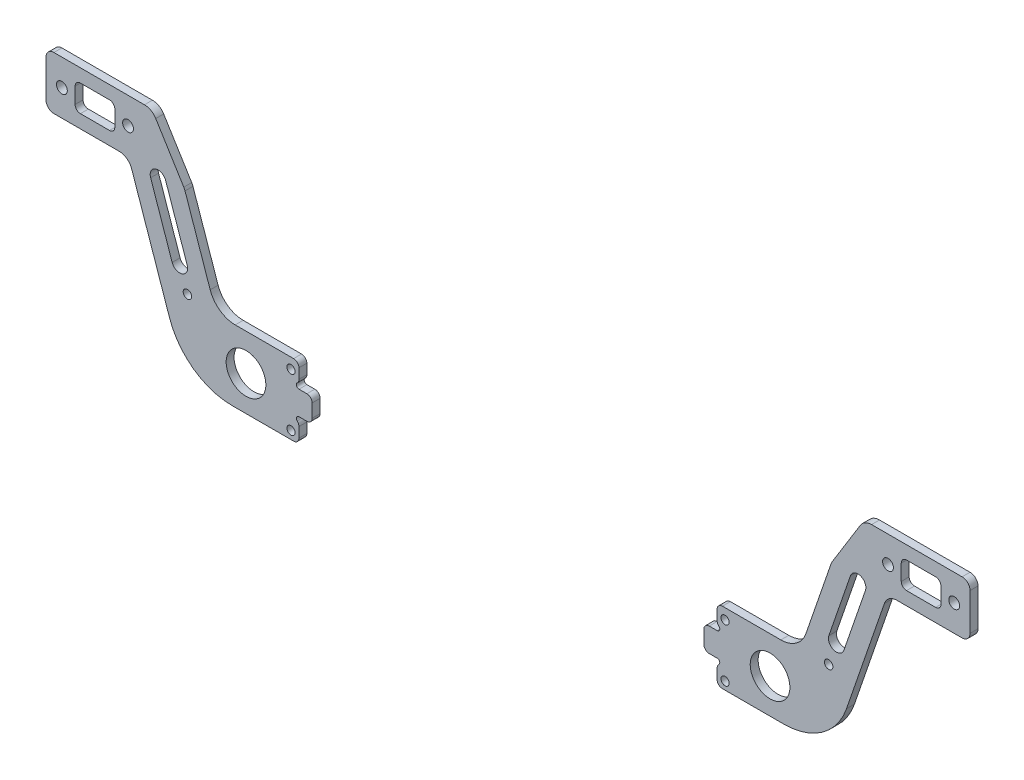
SolidWorks part; units mm, degrees
material "Thornel Mat VMA"
ref_plane "前视基准面" through (0, 0, 0) normal (0, 0, 1) x (1, 0, 0)
ref_plane "上视基准面" through (0, 0, 0) normal (0, 1, 0) x (1, 0, 0)
ref_plane "右视基准面" through (0, 0, 0) normal (1, 0, 0) x (0, 0, -1)
sketch "草图1" plane through (0, 0, 0) normal (0, 0, 1) x (1, 0, 0)
  line L1 (-98, -24.835) -> (98, -24.835)
  line L2 (-98, -24.835) -> (-98, 24.835)
  line L3 (-98, 24.835) -> (98, 24.835)
  line L4 (98, -24.835) -> (98, 24.835)
  line L5 (-98, -24.835) -> (98, 24.835) construction
  line L6 (-98, 24.835) -> (98, -24.835) construction
  point P0 (0, 0)
  dimension "D1" = 196
  dimension "D2" = 49.67
extrude "凸台-拉伸1" add sketch "草图1" along normal blind 3
sketch "草图2" plane through (0, 0, 3) normal (0, 0, 1) x (1, 0, 0)
  line L0 (98, 24.835) -> (114, 24.835)
  line L1 (114, 24.835) -> (122.2225, 48.715)
  line L2 (134.5666, 68.715) -> (174.5666, 68.715)
  line L3 (174.5666, 68.715) -> (174.5666, 48.715)
  line L4 (174.5666, 48.715) -> (143.375, 48.715)
  line L5 (143.375, 48.715) -> (128.2659, 4.835)
  line L6 (128.2659, 4.835) -> (98, 4.835)
  line L7 (98, -24.835) -> (98, 24.835) construction
  line L8 (98, 24.835) -> (98, 4.835)
  line L9 (0, 0) -> (0, 24.835) construction
  line L10 (98, 24.835) -> (-98, 24.835) construction
  line L11 (-98, 24.835) -> (-98, 4.835)
  line L12 (-128.2659, 4.835) -> (-98, 4.835)
  line L13 (-143.375, 48.715) -> (-128.2659, 4.835)
  line L14 (-174.5666, 48.715) -> (-143.375, 48.715)
  line L15 (-174.5666, 68.715) -> (-174.5666, 48.715)
  line L16 (-134.5666, 68.715) -> (-174.5666, 68.715)
  line L17 (-114, 24.835) -> (-122.2225, 48.715)
  line L18 (-98, 24.835) -> (-114, 24.835)
  line L19 (122.2225, 48.715) -> (143.375, 48.715) construction
  line L20 (-122.2225, 48.715) -> (-143.375, 48.715) construction
  line L21 (122.2225, 48.715) -> (134.5666, 68.715)
  line L23 (-122.2225, 48.715) -> (-134.5666, 68.715)
  dimension "D1" = 114
  dimension "D2" = 109
  dimension "D3" = 20
  dimension "D4" = 20
  dimension "D5" = 20
  dimension "D6" = 43.88
  dimension "D7" = 40
  dimension "D8" = 18
extrude "凸台-拉伸2" add sketch "草图2" against normal up to surface (3 mm away) up to face at (0, 0, 0)
fillet "圆角1" radius 10 4 edges at (128.2659, 4.835, 1.5) (114, 24.835, 1.5) (-128.2659, 4.835, 1.5) (-114, 24.835, 1.5)
fillet "圆角2" radius 3 6 edges at (-174.5666, 48.715, 1.5) (-174.5666, 68.715, 1.5) (174.5666, 68.715, 1.5) (174.5666, 48.715, 1.5) (98, -24.835, 1.5) (-98, -24.835, 1.5)
sketch "草图3" plane through (0, 0, 3) normal (0, 0, 1) x (1, 0, 0)
  line L0 (98, -21.835) -> (98, 4.835) construction
  line L1 (-88, -15) -> (88, -15) construction
  line L2 (-88, -15) -> (-88, 15) construction
  line L3 (-88, 15) -> (88, 15) construction
  line L4 (88, -15) -> (88, 15) construction
  line L5 (-88, -15) -> (88, 15) construction
  line L6 (-88, 15) -> (88, -15) construction
  circle A0 centre (88, -15) radius 1.6
  circle A1 centre (88, 15) radius 1.6
  circle A2 centre (-88, 15) radius 1.6
  circle A3 centre (-88, -15) radius 1.6
  point P0 (0, 0)
  dimension "D3" = 3.2
  dimension "D1" = 10
  dimension "D2" = 30
sketch "草图4" plane through (0, 0, 3) normal (0, 0, 1) x (1, 0, 0)
  line L0 (0, 5.1613) -> (0, 0) construction
  line L1 (47.5, -7.3387) -> (-47.5, -7.3387) construction
  line L2 (47.5, -7.3387) -> (47.5, 17.6613) construction
  line L3 (47.5, 17.6613) -> (-47.5, 17.6613) construction
  line L4 (-47.5, -7.3387) -> (-47.5, 17.6613) construction
  line L5 (47.5, -7.3387) -> (-47.5, 17.6613) construction
  line L6 (47.5, 17.6613) -> (-47.5, -7.3387) construction
  circle A2 centre (47.5, -7.3387) radius 2.1
  circle A3 centre (47.5, 17.6613) radius 2.1
  circle A4 centre (-47.5, 17.6613) radius 2.1
  circle A5 centre (-47.5, -7.3387) radius 2.1
  point P6 (0, 5.1613)
  dimension "D4" = 4.2
  dimension "D1" = 95
  dimension "D2" = 25
  dimension "D3" = 5.1613
extrude "切除-拉伸2" cut sketch "草图4" against normal blind 4
fillet "圆角3" radius 5 6 edges at (122.2225, 48.715, 1.5) (-122.2225, 48.715, 1.5) (-134.5666, 68.715, 1.5) (-143.375, 48.715, 1.5) (134.5666, 68.715, 1.5) (143.375, 48.715, 1.5)
sketch "草图5" [suppressed] plane through (0, 0, 4) normal (0, 0, 1) x (1, 0, 0)
  line L0 (0, 0) -> (0, -20.895) construction
  line L1 (0, -20.895) -> (27.5, -20.895) construction
  line L2 (-98, -24.835) -> (98, -24.835) construction
  circle A0 centre (27.5, -20.895) radius 1.55
  circle A1 centre (-27.5, -20.895) radius 1.55
  dimension "D3" = 3.1
  dimension "D1" = 27.5
  dimension "D2" = 3.94
extrude "切除-拉伸3" [suppressed] cut sketch "草图5" against normal blind 10
sketch "草图6" plane through (0, 0, 3) normal (0, 0, 1) x (1, 0, 0)
  line L0 (-174.5666, 58.715) -> (-128.3946, 58.715) construction
  line L1 (-174.5666, 65.715) -> (-174.5666, 51.715) construction
  line L2 (-122.5144, 49.1879) -> (-133.1014, 66.3411) construction
  line L3 (0, 0) -> (0, 128.8135) construction
  line L4 (174.5666, 58.715) -> (128.3946, 58.715) construction
  circle A0 centre (-168.5666, 58.715) radius 2.05
  circle A1 centre (-143.5666, 58.715) radius 2.05
  circle A2 centre (143.5666, 58.715) radius 2.05
  circle A3 centre (168.5666, 58.715) radius 2.05
  dimension "D1" = 4.1
  dimension "D2" = 6
  dimension "D3" = 25
extrude "切除-拉伸4" cut sketch "草图6" against normal blind 10
sketch "草图7" plane through (0, 0, 3) normal (0, 0, 1) x (1, 0, 0)
  line L0 (-174.5666, 58.715) -> (-136.4981, 58.715) construction
  line L1 (-174.5666, 65.715) -> (-174.5666, 51.715) construction
  line L2 (0, 0) -> (0, 175.8145) construction
  line L3 (174.5666, 58.715) -> (136.4981, 58.715) construction
  circle A0 centre (-168.5666, 58.715) radius 2.05
  circle A1 centre (-143.5666, 58.715) radius 2.05
  circle A2 centre (143.5666, 58.715) radius 2.05
  circle A3 centre (168.5666, 58.715) radius 2.05
  dimension "D1" = 4.1
  dimension "D2" = 6
  dimension "D3" = 25
extrude "切除-拉伸5" [suppressed] cut sketch "草图7" against normal blind 102
sketch "草图8" [suppressed] plane through (0, 0, 4) normal (0, 0, 1) x (1, 0, 0)
  line L0 (106.8671, 24.835) -> (-106.8671, 24.835) construction
  line L1 (-40, -15.895) -> (40, -15.895)
  line L2 (-40, -15.895) -> (-40, 18.835)
  line L3 (-40, 18.835) -> (40, 18.835)
  line L4 (40, -15.895) -> (40, 18.835)
  line L5 (-40, -15.895) -> (40, 18.835) construction
  line L6 (-40, 18.835) -> (40, -15.895) construction
  line L7 (0, 1.47) -> (0, 18.835) construction
  line L8 (0, 5.835) -> (-40, -15.895) construction
  line L9 (0, 5.835) -> (40, -15.895) construction
  line L10 (3, 1.47) -> (3, 18.835)
  line L11 (0, 9.2491) -> (41.4321, -13.2589)
  line L12 (0, 9.2491) -> (-41.4321, -13.2589)
  line L13 (-3, 1.47) -> (-3, 18.835)
  line L14 (0, 2.4209) -> (38.5679, -18.5311)
  line L15 (0, 2.4209) -> (-38.5679, -18.5311)
  circle A0 centre (-27.5, -20.895) radius 1.55 construction
  circle A1 centre (-47.5, -7.3387) radius 2.1 construction
  point P0 (0, 1.47)
  dimension "D2" = 7.5
  dimension "D1" = 5
  dimension "D3" = 6
  dimension "D4" = 13
  dimension "D5" = 3
  dimension "D6" = 3
extrude "切除-拉伸8" [suppressed] cut sketch "草图8" against normal blind 10 contours L12 L13 L3 L2 | L14 L15 L1 | L10 L11 L4 L3
fillet "圆角4" [suppressed] radius 3
sketch "草图10" plane through (0, 0, 3) normal (0, 0, 1) x (1, 0, 0)
  line L0 (106.8671, 24.835) -> (-106.8671, 24.835) construction
  line L1 (-40, -17.835) -> (40, -17.835)
  line L2 (-40, -17.835) -> (-40, 18.835)
  line L3 (-40, 18.835) -> (40, 18.835)
  line L4 (40, -17.835) -> (40, 18.835)
  line L5 (-40, -17.835) -> (40, 18.835) construction
  line L6 (-40, 18.835) -> (40, -17.835) construction
  line L7 (-95, -24.835) -> (95, -24.835) construction
  line L8 (0, 18.835) -> (0, 6.835) construction
  line L9 (0, 6.835) -> (-40, -17.835) construction
  line L10 (0, 6.835) -> (40, -17.835) construction
  line L11 (-3, 18.835) -> (-3, 6.835)
  line L12 (-1.5748, 9.3884) -> (-41.5748, -15.2816)
  line L13 (-1.5748, 4.2816) -> (38.4252, -20.3884)
  line L14 (3, 18.835) -> (3, 6.835)
  line L15 (1.5748, 4.2816) -> (-38.4252, -20.3884)
  line L16 (1.5748, 9.3884) -> (41.5748, -15.2816)
  circle A0 centre (-47.5, -7.3387) radius 2.1 construction
  circle A1 centre (47.5, 17.6613) radius 2.1 construction
  point P0 (0, 0.5)
  dimension "D1" = 6
  dimension "D2" = 7
  dimension "D3" = 7.5
  dimension "D4" = 7.5
  dimension "D5" = 12
  dimension "D6" = 3
  dimension "D7" = 3
extrude "切除-拉伸10" cut sketch "草图10" against normal blind 10 contours L13 L15 L1 | L12 L11 L3 L2 | L14 L16 L4 L3
fillet "圆角7" radius 2 11 edges at (-40, 18.835, 1.5) (-3, 18.835, 1.5) (-3, 8.5094, 1.5) (34.2851, -17.835, 1.5) (3, 18.835, 1.5) (40, 18.835, 1.5) (40, -14.3103, 1.5) (3, 8.5094, 1.5) (-34.2851, -17.835, 1.5) (-40, -14.3103, 1.5) (0, 3.3103, 1.5)
sketch "草图13" plane through (0, 0, 3) normal (0, 0, 1) x (1, 0, 0)
  line L0 (106.8671, 24.835) -> (-106.8671, 24.835) construction
  line L1 (-98, 4.835) -> (-104, 4.835)
  line L2 (-98, 4.835) -> (-98, -15.165)
  line L3 (-98, -15.165) -> (-104, -15.165)
  line L4 (-104, 4.835) -> (-104, -15.165)
  dimension "D1" = 40
  dimension "D2" = 6
extrude "凸台-拉伸3" add sketch "草图13" against normal up to surface (3 mm away) up to face at (21.2723, 8.1928, 0)
mirror "镜向3" about plane through (0, 0, 0) normal (1, 0, 0) of "凸台-拉伸3"
fillet "圆角9" radius 10 2 edges at (104, 4.835, 1.5) (-104, 4.835, 1.5)
fillet "圆角10" radius 2 4 edges at (104, -15.165, 1.5) (98, -15.165, 1.5) (-98, -15.165, 1.5) (-104, -15.165, 1.5)
sketch "草图14" plane through (0, 0, 0) normal (0, 0, -1) x (-1, 0, 0)
  line L0 (104, 24.835) -> (104, 9.835) construction
  line L1 (-106.8671, 24.835) -> (106.8671, 24.835) construction
  line L2 (104, 9.835) -> (104, -10.165) construction
  circle A2 centre (104, 9.835) radius 1.55
  circle A3 centre (104, -10.165) radius 1.55
  dimension "D4" = 3.1
  dimension "D1" = 104
  dimension "D2" = 15
  dimension "D3" = 20
extrude "切除-拉伸12" cut sketch "草图14" against normal blind 10
mirror "镜向4" about plane through (0, 0, 0) normal (1, 0, 0) of "切除-拉伸12"
sketch "草图15" [suppressed] plane through (0, 0, 0) normal (0, 0, -1) x (-1, 0, 0)
  line L0 (-106.8671, 24.835) -> (106.8671, 24.835) construction
  line L1 (-101, 4.835) -> (-107, 4.835)
  line L2 (-101, 4.835) -> (-101, -15.165)
  line L3 (-101, -15.165) -> (-107, -15.165)
  line L4 (-107, 4.835) -> (-107, -15.165)
  dimension "D1" = 40
  dimension "D2" = 6
extrude "凸台-拉伸4" [suppressed] add sketch "草图15" against normal up to surface (4 mm away)
mirror "镜向5" [suppressed] about plane through (0, 0, 0) normal (1, 0, 0)
fillet "圆角11" [suppressed] radius 10
fillet "圆角12" [suppressed] radius 2
sketch "草图16" [suppressed] plane through (0, 0, 4) normal (0, 0, 1) x (1, 0, 0)
  line L0 (0, 0) -> (104, 0) construction
  line L1 (104, 0) -> (104, 9.835) construction
  line L2 (104, 0) -> (104, -10.165) construction
  circle A2 centre (104, -10.165) radius 1.6
  circle A3 centre (104, 9.835) radius 1.6
  dimension "D4" = 3.2
  dimension "D1" = 104
  dimension "D2" = 9.835
  dimension "D3" = 10.165
extrude "切除-拉伸13" [suppressed] cut sketch "草图16" against normal blind 10
mirror "镜向6" [suppressed] about plane through (0, 0, 0) normal (1, 0, 0)
sketch "草图21" plane through (0, 0, 3) normal (0, 0, 1) x (1, 0, 0)
  line L0 (-114, 4.835) -> (-98, 4.835)
  line L1 (-98, 4.835) -> (-98, -17.165)
  line L2 (-114, 4.835) -> (-114, -17.165)
  line L3 (-114, -17.165) -> (-98, -17.165)
extrude "切除-拉伸16" cut sketch "草图21" against normal blind 10
sketch "草图22" plane through (0, 0, 3) normal (0, 0, 1) x (1, 0, 0)
  circle A0 centre (-104, 9.835) radius 1.55 construction
  circle A1 centre (-104, 9.835) radius 1.55
extrude "凸台-拉伸5" add sketch "草图22" against normal up to surface (3 mm away) up to face at (17.7653, 26.7306, 0)
fillet "圆角13" radius 10 1 edges at (-98, 4.835, 1.5)
mirror "镜向9" about plane through (0, 0, 0) normal (1, 0, 0) of "切除-拉伸16", "凸台-拉伸5", "圆角13"
sketch "草图23" [suppressed] plane through (0, 0, 4) normal (0, 0, 1) x (1, 0, 0)
  line L0 (-117, 4.835) -> (-101, 4.835)
  line L1 (-101, 4.835) -> (-101, -17.165)
  line L2 (-117, 4.835) -> (-117, -17.165)
  line L3 (-117, -17.165) -> (-101, -17.165)
  line L4 (0, -0.9932) -> (0, 64.1074) construction
  line L5 (117, -17.165) -> (101, -17.165)
  line L6 (117, 4.835) -> (117, -17.165)
  line L7 (101, 4.835) -> (101, -17.165)
  line L8 (117, 4.835) -> (101, 4.835)
extrude "切除-拉伸17" [suppressed] cut sketch "草图23" against normal blind 10
sketch "草图24" [suppressed] plane through (0, 0, 4) normal (0, 0, 1) x (1, 0, 0)
  circle A0 centre (104, 9.835) radius 1.6 construction
  circle A1 centre (-104, 9.835) radius 1.6 construction
  circle A2 centre (104, 9.835) radius 1.6
  circle A3 centre (-104, 9.835) radius 1.6
extrude "凸台-拉伸6" [suppressed] add sketch "草图24" against normal up to surface (4 mm away)
fillet "圆角14" [suppressed] radius 10
sketch "草图25" plane through (0, 0, 3) normal (0, 0, 1) x (1, 0, 0)
  line L0 (-168.7548, 58.715) -> (-143.3784, 58.715) construction
  line L1 (0, 0) -> (0, 119.1313) construction
  line L8 (-163.5666, 53.715) -> (-148.5666, 53.715)
  line L9 (-163.5666, 53.715) -> (-163.5666, 63.715)
  line L10 (-163.5666, 63.715) -> (-148.5666, 63.715)
  line L11 (-148.5666, 53.715) -> (-148.5666, 63.715)
  line L12 (-156.0666, 63.715) -> (-156.0666, 53.715) construction
  line L13 (-163.5666, 58.715) -> (-148.5666, 58.715) construction
  line L14 (163.5666, 63.715) -> (148.5666, 63.715)
  line L15 (148.5666, 53.715) -> (148.5666, 63.715)
  line L16 (163.5666, 53.715) -> (148.5666, 53.715)
  line L17 (163.5666, 53.715) -> (163.5666, 63.715)
  point P2 (-156.0666, 58.715)
extrude "切除-拉伸18" cut sketch "草图25" against normal blind 10
sketch "草图26" plane through (0, 0, 3) normal (0, 0, 1) x (1, 0, 0)
  line L0 (116.3223, 31.5793) -> (110.2124, 13.835)
  line L1 (-98, 35) -> (98, 35)
  line L2 (-98, 35) -> (-98, -35)
  line L3 (-98, -35) -> (98, -35)
  line L4 (98, 35) -> (98, -35)
  line L5 (-98, 35) -> (98, -35) construction
  line L6 (-98, -35) -> (98, 35) construction
  line L7 (130.5881, 11.5793) -> (122.068, -13.165)
  line L8 (130.5881, 11.5793) -> (142.2138, 45.3428) construction
  line L9 (122.068, -13.165) -> (74, -13.165)
  line L10 (74, -13.165) -> (74, 13.835)
  line L11 (74, 13.835) -> (110.2124, 13.835)
  line L12 (130.5881, 11.5793) -> (116.3223, 31.5793)
  line L13 (106.8671, 24.835) -> (-106.8671, 24.835) construction
  line L14 (106.8671, 24.835) -> (-106.8671, 24.835)
  line L15 (0, -63.4522) -> (0, 61.7142) construction
  line L16 (122.0416, 48.1896) -> (116.3223, 31.5793) construction
  line L17 (-130.5881, 11.5793) -> (-122.068, -13.165)
  line L18 (-122.068, -13.165) -> (-74, -13.165)
  line L19 (-74, -13.165) -> (-74, 13.835)
  line L20 (-74, 13.835) -> (-110.2124, 13.835)
  line L21 (-116.3223, 31.5793) -> (-110.2124, 13.835)
  line L22 (-130.5881, 11.5793) -> (-116.3223, 31.5793)
  line L23 (98, -21.835) -> (98, -5.165) construction
  arc A0 (-116.3223, 31.5793) -> (-106.8671, 24.835) centre (-106.8671, 34.835) ccw construction
  arc A1 (106.8671, 24.835) -> (116.3223, 31.5793) centre (106.8671, 34.835) ccw construction
  arc A2 (-116.3223, 31.5793) -> (-106.8671, 24.835) centre (-106.8671, 34.835) ccw
  arc A3 (106.8671, 24.835) -> (116.3223, 31.5793) centre (106.8671, 34.835) ccw
  point P0 (0, 0)
  dimension "D1" = 27
  dimension "D2" = 24
  dimension "D3" = 11
  dimension "D4" = 70
extrude "切除-拉伸19" cut sketch "草图26" against normal mid plane 10 contours L20 L19 L18 L2 L3 L4 L9 L10 L11 L14 | A3 L14 L4 L11 L0 | A2 L21 L20 L2 L14
sketch "草图27" plane through (0, 0, 3) normal (0, 0, 1) x (1, 0, 0)
  line L14 (116.3223, 31.5793) -> (110.2124, 13.835)
  line L15 (110.2124, 13.835) -> (74, 13.835)
  line L16 (74, 13.835) -> (74, -13.165)
  line L17 (74, -13.165) -> (122.068, -13.165)
  line L18 (122.068, -13.165) -> (130.5881, 11.5793)
  line L19 (130.5881, 11.5793) -> (116.3223, 31.5793)
  line L20 (116.3223, 31.5793) -> (112.5347, 20.5793)
  line L21 (103.0795, 13.835) -> (74, 13.835)
  line L22 (74, 13.835) -> (74, -13.165)
  line L23 (74, -13.165) -> (104.2356, -13.165)
  line L24 (127.8736, 3.6958) -> (130.5881, 11.5793)
  line L25 (130.5881, 11.5793) -> (116.3223, 31.5793)
  line L26 (-130.5881, 11.5793) -> (-122.068, -13.165)
  line L27 (-122.068, -13.165) -> (-74, -13.165)
  line L28 (-74, -13.165) -> (-74, 13.835)
  line L29 (-74, 13.835) -> (-110.2124, 13.835)
  line L30 (-110.2124, 13.835) -> (-116.3223, 31.5793)
  line L31 (-116.3223, 31.5793) -> (-130.5881, 11.5793)
  line L32 (-130.5881, 11.5793) -> (-127.8736, 3.6958)
  line L33 (-104.2356, -13.165) -> (-74, -13.165)
  line L34 (-74, -13.165) -> (-74, 13.835)
  line L35 (-74, 13.835) -> (-103.0795, 13.835)
  line L36 (-112.5347, 20.5793) -> (-116.3223, 31.5793)
  line L37 (-116.3223, 31.5793) -> (-130.5881, 11.5793)
  arc A1 (112.5347, 20.5793) -> (103.0795, 13.835) centre (103.0795, 23.835) cw
  arc A3 (-103.0795, 13.835) -> (-112.5347, 20.5793) centre (-103.0795, 23.835) cw
  arc A4 (-127.8736, 3.6958) -> (-104.2356, -13.165) centre (-104.2356, 11.835) ccw
  arc A5 (104.2356, -13.165) -> (127.8736, 3.6958) centre (104.2356, 11.835) ccw
  dimension "D4" = 10
  dimension "D5" = 25
  dimension "D2" = 0
  dimension "D3" = 0
extrude "凸台-拉伸7" add sketch "草图27" against normal blind 3
sketch "草图28" plane through (0, 0, 3) normal (0, 0, 1) x (1, 0, 0)
  line L0 (106.8671, 24.835) -> (-106.8671, 24.835) construction
  line L1 (106.8671, 24.835) -> (-106.8671, 24.835)
  line L2 (82, -10.165) -> (82, 9.835) construction
  line L3 (0, -63.4522) -> (0, 61.7142) construction
  line L4 (98, 35) -> (-98, 35)
  line L5 (98, -35) -> (98, 35)
  line L6 (-98, -35) -> (98, -35)
  line L7 (-98, 35) -> (-98, -35)
  line L8 (98, 35) -> (-98, 35)
  line L9 (98, -35) -> (98, 35)
  line L10 (-98, -35) -> (98, -35)
  line L11 (-98, 35) -> (-98, -35)
  line L12 (0, -63.4522) -> (0, 61.7142)
  line L14 (116.3223, 31.5793) -> (110.2124, 13.835)
  line L15 (110.2124, 13.835) -> (74, 13.835)
  line L16 (74, 13.835) -> (74, -13.165)
  line L17 (74, -13.165) -> (122.068, -13.165)
  line L18 (122.068, -13.165) -> (130.5881, 11.5793)
  line L19 (130.5881, 11.5793) -> (116.3223, 31.5793)
  line L20 (116.3223, 31.5793) -> (110.2124, 13.835)
  line L21 (110.2124, 13.835) -> (74, 13.835)
  line L22 (74, 13.835) -> (74, -13.165)
  line L23 (74, -13.165) -> (122.068, -13.165)
  line L24 (122.068, -13.165) -> (130.5881, 11.5793)
  line L25 (130.5881, 11.5793) -> (116.3223, 31.5793)
  line L26 (-130.5881, 11.5793) -> (-122.068, -13.165)
  line L27 (-122.068, -13.165) -> (-74, -13.165)
  line L28 (-74, -13.165) -> (-74, 13.835)
  line L29 (-74, 13.835) -> (-110.2124, 13.835)
  line L30 (-110.2124, 13.835) -> (-116.3223, 31.5793)
  line L31 (-116.3223, 31.5793) -> (-130.5881, 11.5793)
  line L32 (-130.5881, 11.5793) -> (-122.068, -13.165)
  line L33 (-122.068, -13.165) -> (-74, -13.165)
  line L34 (-74, -13.165) -> (-74, 13.835)
  line L35 (-74, 13.835) -> (-110.2124, 13.835)
  line L36 (-110.2124, 13.835) -> (-116.3223, 31.5793)
  line L37 (-116.3223, 31.5793) -> (-130.5881, 11.5793)
  arc A0 (-116.3223, 31.5793) -> (-106.8671, 24.835) centre (-106.8671, 34.835) ccw construction
  arc A1 (106.8671, 24.835) -> (116.3223, 31.5793) centre (106.8671, 34.835) ccw construction
  arc A2 (-116.3223, 31.5793) -> (-106.8671, 24.835) centre (-106.8671, 34.835) ccw
  arc A3 (106.8671, 24.835) -> (116.3223, 31.5793) centre (106.8671, 34.835) ccw
  circle A4 centre (82, 9.835) radius 1.55
  circle A5 centre (82, -10.165) radius 1.55
  circle A6 centre (-82, 9.835) radius 1.55
  circle A7 centre (-82, -10.165) radius 1.55
  dimension "D6" = 3.1
  dimension "D4" = 8
  dimension "D5" = 20
  dimension "D7" = 15
  dimension "D1" = 0
  dimension "D2" = 0
  dimension "D3" = 0
extrude "切除-拉伸20" cut sketch "草图28" against normal blind 3 contours A4 | A5 | A7 | A6
sketch "草图29" plane through (0, 0, 3) normal (0, 0, 1) x (1, 0, 0)
  line L0 (0, -27.1496) -> (0, 41.7148) construction
  line L1 (74, 13.835) -> (79, 13.835)
  line L2 (74, 13.835) -> (74, 4.835)
  line L3 (74, 4.835) -> (79, 4.835)
  line L4 (79, 13.835) -> (79, 4.835)
  line L5 (74, -13.165) -> (79, -13.165)
  line L6 (74, -13.165) -> (74, -4.165)
  line L7 (74, -4.165) -> (79, -4.165)
  line L8 (79, -13.165) -> (79, -4.165)
  line L9 (-79, -13.165) -> (-79, -4.165)
  line L10 (-74, -4.165) -> (-79, -4.165)
  line L11 (-74, -13.165) -> (-74, -4.165)
  line L12 (-74, -13.165) -> (-79, -13.165)
  line L13 (-79, 13.835) -> (-79, 4.835)
  line L14 (-74, 4.835) -> (-79, 4.835)
  line L15 (-74, 13.835) -> (-74, 4.835)
  line L16 (-74, 13.835) -> (-79, 13.835)
  circle A0 centre (79, 5.835) radius 1
  circle A1 centre (79, -5.165) radius 1
  circle A2 centre (-79, -5.165) radius 1
  circle A3 centre (-79, 5.835) radius 1
  line M20 (103.0795, 13.835) -> (74, 13.835)
  line M21 (74, 13.835) -> (74, -13.165)
  line M22 (74, -13.165) -> (104.2356, -13.165)
  dimension "D3" = 2
  dimension "D1" = 5
  dimension "D2" = 9
extrude "切除-拉伸21" cut sketch "草图29" against normal blind 5 contours A1 L7 L8 M21 M22 | L8 A1 | L8 A1 | A0 L4 L3 M20 M21 | L4 A0 | L4 A0 | L13 A3 L14 L15 L16 | A3 L13 | A3 L13 | A2 L9 | A2 L9 | L10 A2 L9 L12 L11
sketch "草图30" plane through (0, 0, 0) normal (0, 0, -1) x (-1, 0, 0)
  circle A0 centre (121.1329, 14.835) radius 1.6
  circle A1 centre (-121.1329, 14.835) radius 1.6
  dimension "D1" = 3.2
extrude "切除-拉伸22" cut sketch "草图30" against normal blind 10
fillet "圆角15" radius 2 10 edges at (-148.5666, 53.715, 1.5) (-163.5666, 53.715, 1.5) (-148.5666, 63.715, 1.5) (-79, 13.835, 1.5) (-79, -13.165, 1.5) (-79, -6.165, 1.5) (-74, -4.165, 1.5) (-74, 4.835, 1.5) (-79, 6.835, 1.5) (-163.5666, 63.715, 1.5)
sketch "草图31" plane through (0, 0, 3) normal (0, 0, 1) x (1, 0, 0)
  line L0 (-132.2022, 46.9826) -> (-124.063, 23.3447) construction
  line L1 (-129.3657, 47.9593) -> (-121.2265, 24.3214)
  line L2 (-135.0388, 46.0059) -> (-126.8996, 22.368)
  line L3 (-121.1329, 14.835) -> (-142.3033, 76.3181) construction
  line L4 (-142.2138, 45.3428) -> (-127.8736, 3.6958) construction
  line L5 (0, -55.3652) -> (0, 55.1106) construction
  line L6 (132.2022, 46.9826) -> (124.063, 23.3447) construction
  line L7 (129.3657, 47.9593) -> (121.2265, 24.3214)
  line L8 (135.0388, 46.0059) -> (126.8996, 22.368)
  line L9 (121.1329, 14.835) -> (142.3033, 76.3181) construction
  arc A0 (-129.3657, 47.9593) -> (-135.0388, 46.0059) centre (-132.2022, 46.9826) ccw
  arc A1 (-126.8996, 22.368) -> (-121.2265, 24.3214) centre (-124.063, 23.3447) ccw
  circle A2 centre (-99, 0) radius 7.5
  arc A3 (129.3657, 47.9593) -> (135.0388, 46.0059) centre (132.2022, 46.9826) cw
  arc A4 (126.8996, 22.368) -> (121.2265, 24.3214) centre (124.063, 23.3447) cw
  circle A5 centre (99, 0) radius 7.5
  point P2 (-128.1326, 35.1636)
  point P19 (128.1326, 35.1636)
  dimension "D1" = 3
  dimension "D5" = 15
  dimension "D2" = 9
  dimension "D3" = 25
  dimension "D4" = 99
extrude "切除-拉伸23" cut sketch "草图31" against normal blind 10
fillet "圆角16" radius 2 10 edges at (163.5666, 53.715, 1.5) (148.5666, 53.715, 1.5) (163.5666, 63.715, 1.5) (79, -13.165, 1.5) (79, 13.835, 1.5) (79, 6.835, 1.5) (74, 4.835, 1.5) (74, -4.165, 1.5) (79, -6.165, 1.5) (148.5666, 63.715, 1.5)
